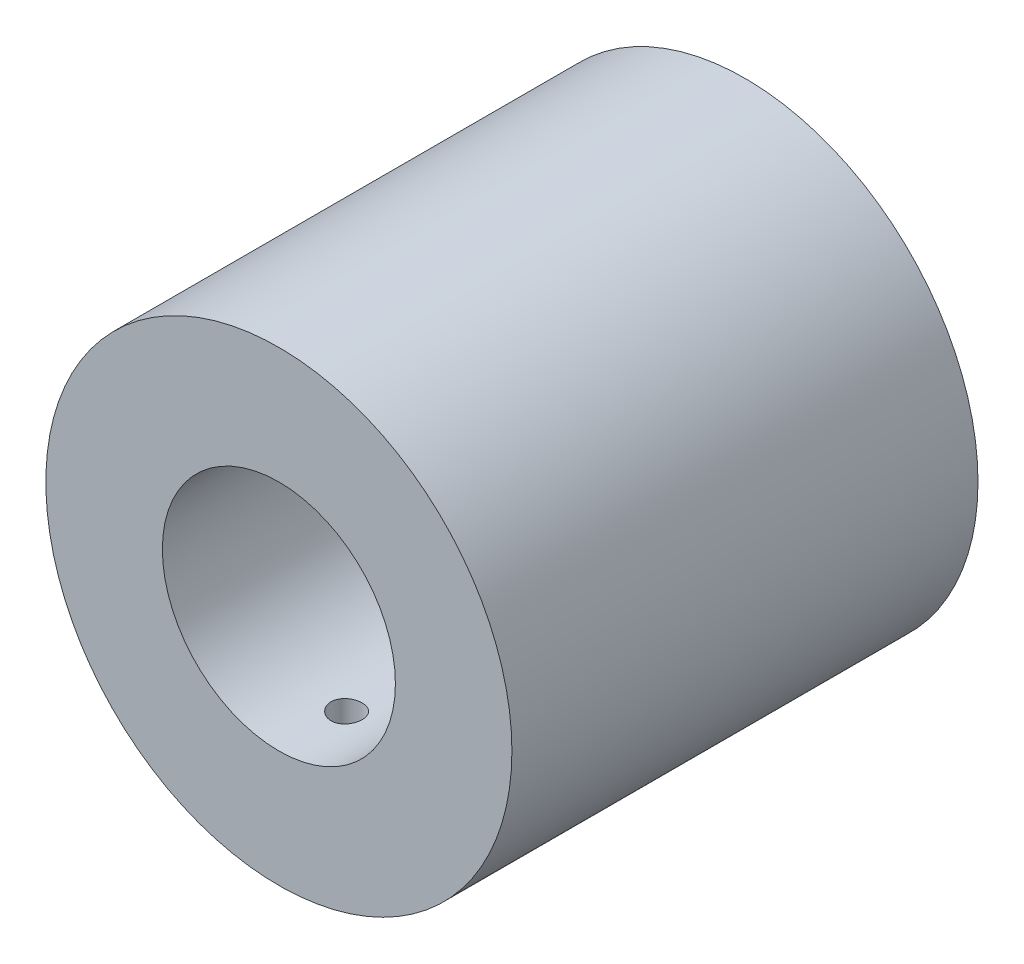
SolidWorks part; units mm, degrees
ref_plane "前视基准面" through (0, 0, 0) normal (0, 0, 1) x (1, 0, 0)
ref_plane "上视基准面" through (0, 0, 0) normal (0, 1, 0) x (1, 0, 0)
ref_plane "右视基准面" through (0, 0, 0) normal (1, 0, 0) x (0, 0, -1)
sketch "草图1" plane through (0, 0, 0) normal (0, 0, 1) x (1, 0, 0)
  circle A0 centre (0, 0) radius 7.5
  circle A1 centre (0, 0) radius 15
  dimension "D1" = 15
  dimension "D2" = 30
extrude "凸台-拉伸1" add sketch "草图1" along normal blind 30
sketch "草图2" plane through (0, 0, 0) normal (0, 1, 0) x (1, 0, 0)
  line L0 (-15, -15) -> (15, -15) construction
  line L1 (-15, 0) -> (-15, -30) construction
  line L2 (15, -30) -> (15, 0) construction
  circle A0 centre (0, -25.639) radius 1
  circle A1 centre (0, -4.361) radius 1
  dimension "D1" = 2
extrude "切除-拉伸1" cut sketch "草图2" against normal blind 30
